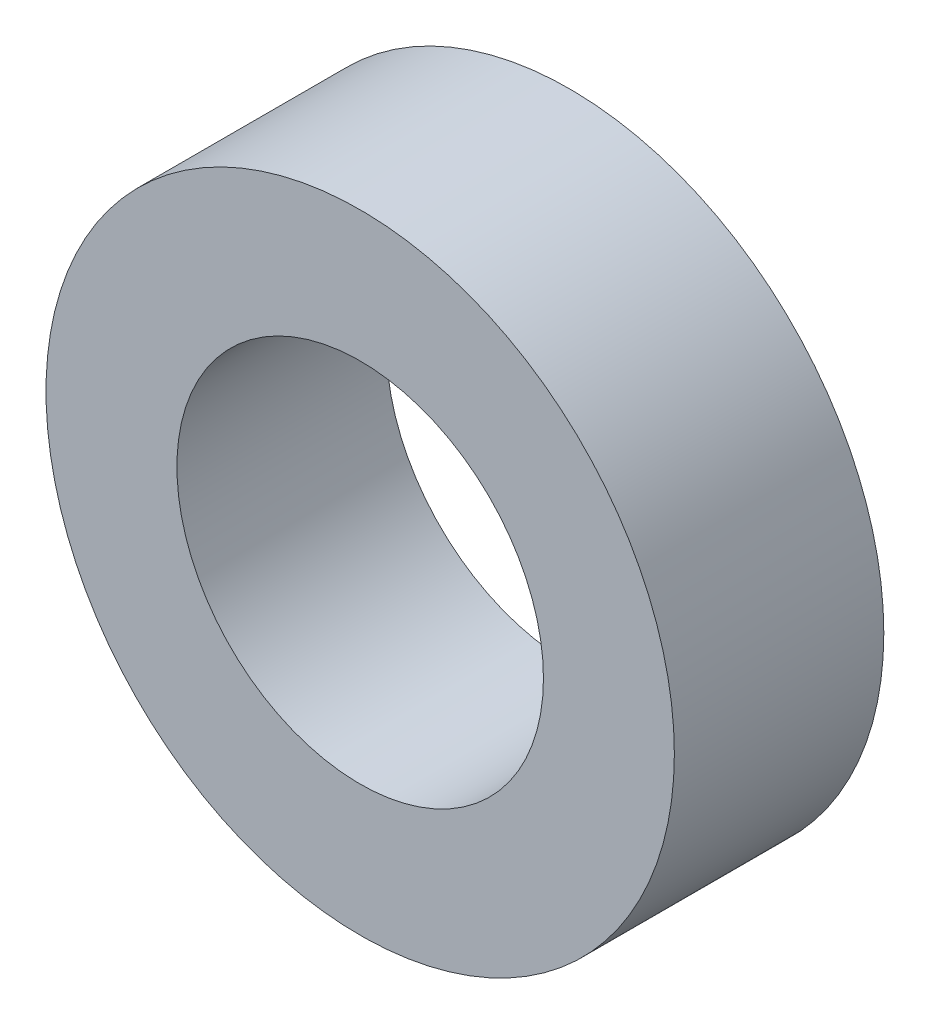
SolidWorks part; units mm, degrees
material "ABS"
ref_plane "Спереди" through (0, 0, 0) normal (0, 0, 1) x (1, 0, 0)
ref_plane "Сверху" through (0, 0, 0) normal (0, 1, 0) x (1, 0, 0)
ref_plane "Справа" through (0, 0, 0) normal (1, 0, 0) x (0, 0, -1)
sketch "Эскиз1" plane through (0, 0, 0) normal (0, 0, 1) x (1, 0, 0)
  circle A0 centre (0, 0) radius 1.75
  circle A1 centre (0, 0) radius 3
  dimension "D1" = 3.5
  dimension "D2" = 6
extrude "Бобышка-Вытянуть1" add sketch "Эскиз1" along normal blind 2
